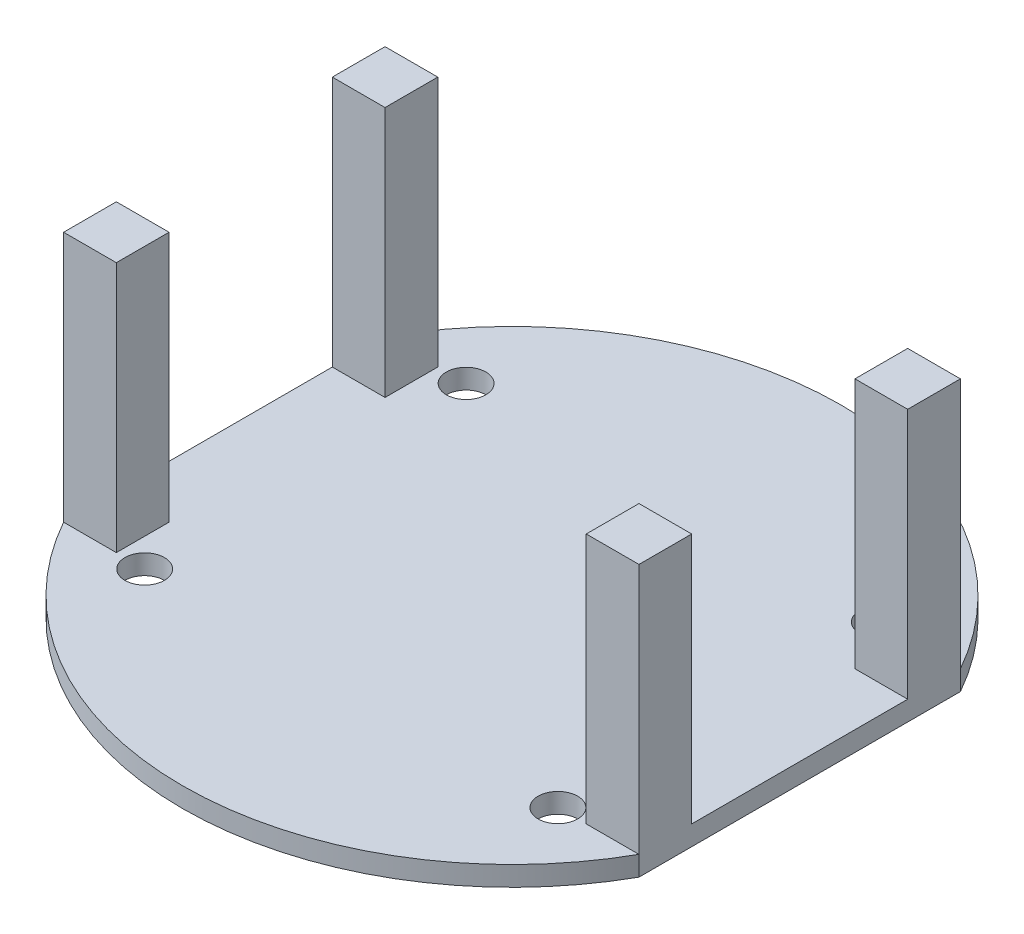
SolidWorks part; units mm, degrees
ref_plane "Front Plane" through (0, 0, 0) normal (0, 0, 1) x (1, 0, 0)
ref_plane "Top Plane" through (0, 0, 0) normal (0, 1, 0) x (1, 0, 0)
ref_plane "Right Plane" through (0, 0, 0) normal (1, 0, 0) x (0, 0, -1)
sketch "Sketch2" plane through (0, 0, 0) normal (0, 1, 0) x (1, 0, 0)
  circle A0 centre (0, 0) radius 50
  dimension "D1" = 100
extrude "Boss-Extrude1" add sketch "Sketch2" along normal blind 3
sketch "Sketch6" plane through (0, 3, 0) normal (0, 1, 0) x (1, 0, 0)
  line L0 (0, 0) -> (-50, 0) construction
  line L1 (-43.65, 0) -> (-43.65, 24.386) construction
  line L2 (0, 0) -> (50, 0) construction
  line L3 (43.65, 24.386) -> (43.65, 0) construction
  line L4 (-43.65, 24.386) -> (-43.65, -24.386)
  line L5 (43.65, 24.386) -> (43.65, -24.386)
  line L6 (-43.65, 24.386) -> (-50, 24.386)
  line L7 (-50, 24.386) -> (-50, 0)
  line L8 (-50, 0) -> (-50, -24.386)
  line L9 (-50, -24.386) -> (-43.65, -24.386)
  line L10 (43.65, -24.386) -> (50, -24.386)
  line L11 (50, -24.386) -> (50, 0)
  line L12 (50, 0) -> (50, 24.386)
  line L13 (50, 24.386) -> (43.65, 24.386)
  circle A0 centre (0, 0) radius 50 construction
  dimension "D1" = 6.35
  dimension "D2" = 6.35
extrude "Cut-Extrude1" cut sketch "Sketch6" against normal blind 38.1
sketch "Sketch9" plane through (0, 3, 0) normal (0, 1, 0) x (1, 0, 0)
  line L6 (-43.65, 24.386) -> (-35.65, 24.386)
  line L7 (-43.65, 24.386) -> (-43.65, 16.386)
  line L8 (-43.65, 16.386) -> (-35.65, 16.386)
  line L9 (-35.65, 24.386) -> (-35.65, 16.386)
  line L10 (43.65, 24.386) -> (35.65, 24.386)
  line L11 (43.65, 24.386) -> (43.65, 16.386)
  line L12 (43.65, 16.386) -> (35.65, 16.386)
  line L13 (35.65, 24.386) -> (35.65, 16.386)
  line L14 (43.65, -24.386) -> (35.65, -24.386)
  line L15 (43.65, -24.386) -> (43.65, -16.386)
  line L16 (43.65, -16.386) -> (35.65, -16.386)
  line L17 (35.65, -24.386) -> (35.65, -16.386)
  line L18 (-43.65, -24.386) -> (-35.65, -24.386)
  line L19 (-43.65, -24.386) -> (-43.65, -16.386)
  line L20 (-43.65, -16.386) -> (-35.65, -16.386)
  line L21 (-35.65, -24.386) -> (-35.65, -16.386)
  dimension "D1" = 8
  dimension "D3" = 8
  dimension "D4" = 8
  dimension "D5" = 8
  dimension "D6" = 8
  dimension "D7" = 8
  dimension "D8" = 8
extrude "Boss-Extrude2" add sketch "Sketch9" along normal blind 38.1
sketch "Sketch10" plane through (0, 0, 0) normal (0, -1, 0) x (-1, 0, 0)
  line L0 (-43.65, -24.386) -> (43.65, -24.386) construction
  line L1 (43.65, 24.386) -> (-43.65, 24.386) construction
  line L2 (-19.05, -50.8) -> (-43.65, -24.386) construction
  line L3 (-43.65, -24.386) -> (-19.05, -24.386) construction
  line L4 (-19.05, -50.8) -> (-19.05, 50.8) construction
  line L5 (-19.05, -24.386) -> (-31.35, -24.386) construction
  line L6 (-31.35, -24.386) -> (-31.35, 24.386) construction
  line L7 (19.05, 50.8) -> (43.65, 24.386) construction
  line L8 (19.05, 50.8) -> (19.05, 24.386) construction
  line L9 (19.05, -50.8) -> (19.05, 50.8) construction
  line L10 (19.05, 24.386) -> (43.65, 24.386) construction
  line L11 (43.65, 24.386) -> (31.35, 24.386) construction
  line L12 (31.35, 24.386) -> (31.35, -24.386) construction
  circle A0 centre (31.35, -24.386) radius 3
  circle A1 centre (31.35, 24.386) radius 3
  circle A2 centre (-31.35, 24.386) radius 3
  circle A3 centre (-31.35, -24.386) radius 3
  dimension "D1" = 6
  dimension "D2" = 6
  dimension "D3" = 6
  dimension "D4" = 6
extrude "Cut-Extrude2" cut sketch "Sketch10" against normal up to surface (3 mm away) up to face at (0, 3, 0)
equation "\"2.2mmmm\"=10"
